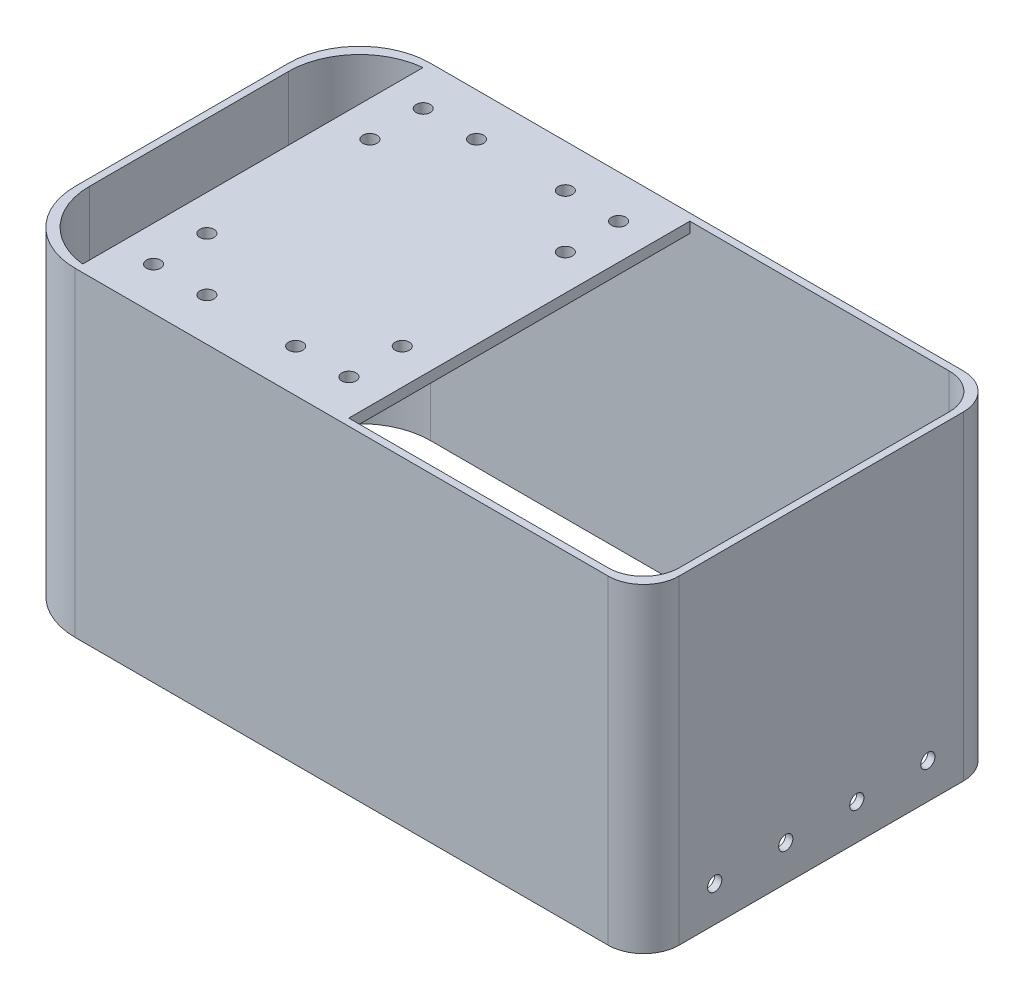
SolidWorks part; units mm, degrees
ref_plane "Ön Düzlem" through (0, 0, 0) normal (0, 0, 1) x (1, 0, 0)
ref_plane "Üst Düzlem" through (0, 0, 0) normal (0, 1, 0) x (1, 0, 0)
ref_plane "Sağ Düzlem" through (0, 0, 0) normal (1, 0, 0) x (0, 0, -1)
sketch "Çizim1" plane through (0, 0, 0) normal (0, 1, 0) x (1, 0, 0)
  line L1 (-70, -50) -> (80, -50)
  line L2 (-90, -30) -> (-90, 30)
  line L3 (-70, 50) -> (80, 50)
  line L4 (90, -40) -> (90, 40)
  line L5 (-90, -50) -> (90, 50) construction
  line L6 (-90, 50) -> (90, -50) construction
  line L7 (0, 48) -> (78, 48)
  line L8 (88, 0) -> (88, -38)
  line L9 (88, 38) -> (88, 0)
  line L11 (-68, -48) -> (78, -48)
  line L12 (0, 48) -> (-68, 48)
  line L14 (-88, 28) -> (-88, -28)
  arc A0 (-88, -28) -> (-68, -48) centre (-68, -28) ccw
  arc A1 (-68, 48) -> (-88, 28) centre (-68, 28) ccw
  arc A2 (-70, -50) -> (-90, -30) centre (-70, -30) cw
  arc A3 (-90, 30) -> (-70, 50) centre (-70, 30) cw
  arc A4 (88, -38) -> (78, -48) centre (78, -38) cw
  arc A5 (78, 48) -> (88, 38) centre (78, 38) cw
  arc A6 (80, -50) -> (90, -40) centre (80, -40) ccw
  arc A7 (80, 50) -> (90, 40) centre (80, 40) cw
  point P0 (0, 0)
  dimension "D1" = 20
  dimension "D2" = 20
  dimension "D3" = 10
  dimension "D4" = 10
extrude "Yükseklik-Ekstrüzyon1" add sketch "Çizim1" along normal blind 90
sketch "Çizim2" plane through (0, 90, 0) normal (0, 1, 0) x (1, 0, 0)
  line L0 (5, 50) -> (5, -50)
  line L1 (80, 50) -> (-70, 50) construction
  line L2 (-70, -50) -> (80, -50) construction
  line L3 (5, -50) -> (-70, -50)
  line L4 (-70, -50) -> (-70, 50)
  line L5 (-70, 50) -> (5, 50)
  dimension "D1" = 75
  dimension "D2" = 100
extrude "Yükseklik-Ekstrüzyon2" add sketch "Çizim2" against normal blind 3
sketch "Çizim3" plane through (-90, 0, 0) normal (-1, 0, 0) x (0, 0, 1)
  circle A0 centre (-20, 10) radius 2
  circle A1 centre (-10, 10) radius 2
  circle A2 centre (0, 10) radius 2
  circle A3 centre (10, 10) radius 2
  circle A4 centre (20, 10) radius 2
extrude "Kes-Ekstrüzyon1" cut sketch "Çizim3" against normal blind 10
sketch "Çizim4" plane through (0, 90, 0) normal (0, 1, 0) x (1, 0, 0)
  line L4 (-70, 47.8997) -> (5, 48)
  line L6 (-70, -47.8997) -> (5, -48)
  circle A0 centre (-60, 37.9499) radius 2
  circle A1 centre (-45, 37.9499) radius 2
  circle A2 centre (-60, 22.9499) radius 2
  circle A3 centre (-5, 22.9499) radius 2
  circle A4 centre (-20, 37.9499) radius 2
  circle A5 centre (-5, 37.9499) radius 2
  circle A6 centre (-5, -37.9499) radius 2
  circle A7 centre (-20, -37.9499) radius 2
  circle A8 centre (-5, -22.9499) radius 2
  circle A9 centre (-60, -22.9499) radius 2
  circle A10 centre (-45, -37.9499) radius 2
  circle A11 centre (-60, -37.9499) radius 2
  point P0 (0, 0)
extrude "Kes-Ekstrüzyon2" cut sketch "Çizim4" against normal blind 10 contours A2 | A0 | A1 | A4 | A5 | A3 | A8 | A6 | A7 | A10 | A11 | A9
sketch "Çizim5" plane through (90, 0, 0) normal (1, 0, 0) x (0, 0, -1)
  circle A0 centre (-30, 10) radius 2
  circle A1 centre (-10, 10) radius 2
  circle A2 centre (10, 10) radius 2
  circle A3 centre (30, 10) radius 2
extrude "Kes-Ekstrüzyon3" cut sketch "Çizim5" against normal blind 10
